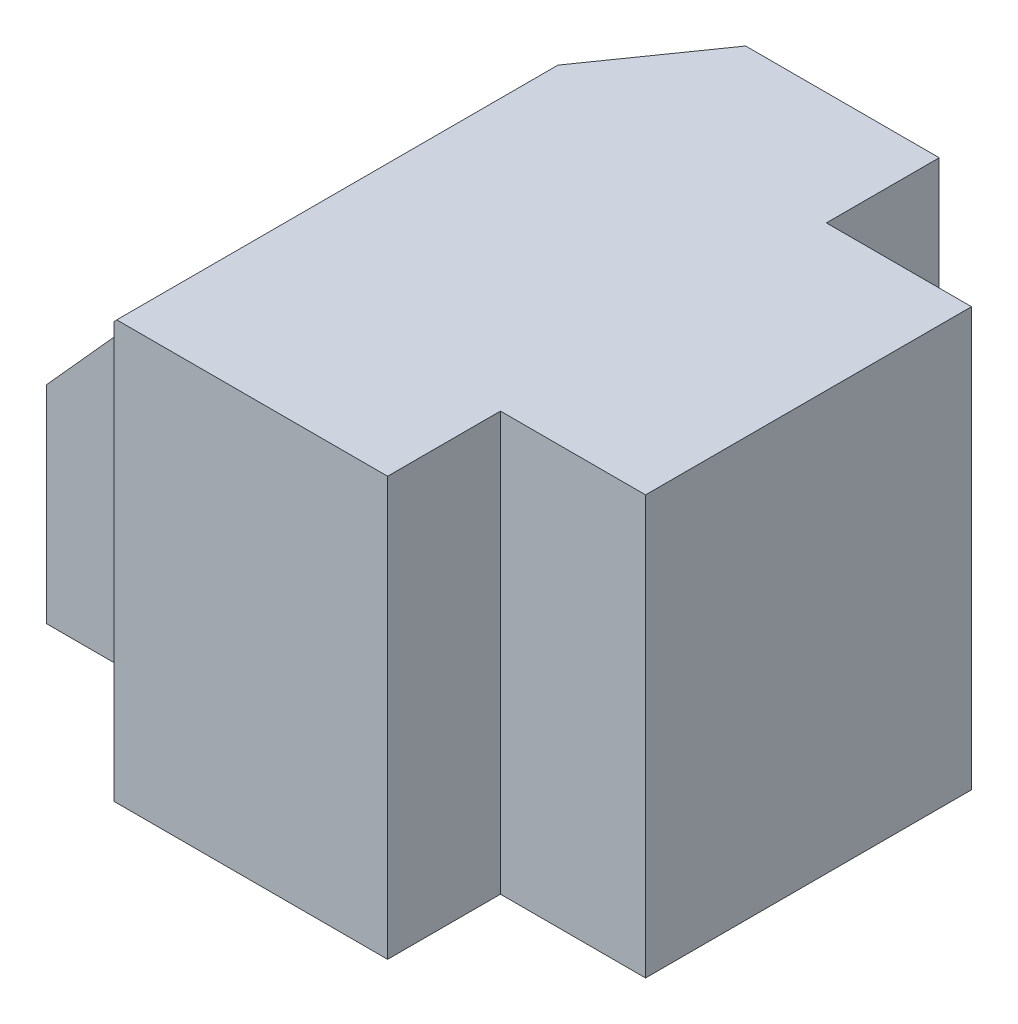
SolidWorks part; units mm, degrees
ref_plane "Front Plane" through (0, 0, 0) normal (0, 0, 1) x (1, 0, 0)
ref_plane "Top Plane" through (0, 0, 0) normal (0, 1, 0) x (1, 0, 0)
ref_plane "Right Plane" through (0, 0, 0) normal (1, 0, 0) x (0, 0, -1)
sketch "Sketch1" plane through (0, 0, 0) normal (0, 1, 0) x (1, 0, 0)
  line L0 (-131.505, 0) -> (131.505, 0) construction
  line L1 (-92.1519, -53.8673) -> (-92.1519, 53.8673)
  line L2 (-92.1519, 53.8673) -> (-27.2957, 53.8673)
  line L3 (-27.2957, 53.8673) -> (-27.2957, -53.8673)
  line L4 (-27.2957, 53.8673) -> (-27.2957, 95.4406)
  line L5 (-27.2957, 95.4406) -> (67.4596, 95.4406)
  line L6 (67.4596, 95.4406) -> (67.4596, -95.4406)
  line L7 (67.4596, 56.3956) -> (117.6766, 56.3956)
  line L8 (117.6766, 56.3956) -> (117.6766, -56.3956)
  line L9 (67.4596, -56.3956) -> (117.6766, -56.3956)
  line L10 (-27.2957, -95.4406) -> (67.4596, -95.4406)
  line L11 (-27.2957, -53.8673) -> (-27.2957, -95.4406)
  line L12 (-92.1519, -53.8673) -> (-27.2957, -53.8673)
  point P4 (0, 0)
  point P15 (117.6766, 0)
  point P16 (67.4596, 0)
  point P17 (-27.2957, 0)
  point P18 (-92.1519, 0)
extrude "Boss-Extrude1" add sketch "Sketch1" along normal blind 144.78 contours L0 L1 L12 L3 | L1 L0 L3 L2 | L3 L0 L6 L5 L4 | L0 L3 L11 L10 L6 | L6 L0 L8 L7 | L0 L6 L9 L8
chamfer "Chamfer1" distance 65.88 angle 48 1 edges at (-92.1519, 144.78, 0)
chamfer "Chamfer2" distance 27.78 angle 55 1 edges at (-27.2957, 71.8215, -95.4406)
sketch "Sketch2" plane through (0, 0, -53.8673) normal (0, 0, -1) x (-1, 0, 0)
  line L4 (92.1519, 0) -> (92.1519, 71.6128)
  line L5 (92.1519, 71.6128) -> (27.2957, 143.6429)
  line L6 (27.2957, 143.6429) -> (27.2957, 0)
  line L7 (27.2957, 0) -> (92.1519, 0)
  line L8 (92.1519, 0) -> (92.1519, 71.6128)
  line L9 (92.1519, 71.6128) -> (27.2957, 143.6429)
  line L10 (27.2957, 143.6429) -> (27.2957, 0)
  line L11 (27.2957, 0) -> (92.1519, 0)
  dimension "D1" = 0
sketch "Sketch3" plane through (-44.5174, 0, -31.1714) normal (-0.8192, 0, -0.5736) x (-0.5736, 0, 0.8192)
  line L5 (-31.8101, 144.78) -> (-78.4581, 144.78)
  line L6 (-78.4581, 144.78) -> (-78.4581, 0)
  line L7 (-78.4581, 0) -> (-30.0252, 0)
  line L8 (-30.0252, 0) -> (-30.0252, 143.6429)
  line L9 (-30.0252, 143.6429) -> (-31.8101, 144.78)
  line L10 (-31.8101, 144.78) -> (-78.4581, 144.78)
  line L11 (-78.4581, 144.78) -> (-78.4581, 0)
  line L12 (-78.4581, 0) -> (-30.0252, 0)
  line L13 (-30.0252, 0) -> (-30.0252, 143.6429)
  line L14 (-30.0252, 143.6429) -> (-31.8101, 144.78)
  dimension "D1" = 0
sketch "Sketch4" plane through (0, 0, -95.4406) normal (0, 0, -1) x (-1, 0, 0)
  line L4 (-67.4596, 0) -> (-0.4843, 0)
  line L5 (-0.4843, 0) -> (-0.4843, 144.78)
  line L6 (-0.4843, 144.78) -> (-67.4596, 144.78)
  line L7 (-67.4596, 144.78) -> (-67.4596, 0)
  line L8 (-67.4596, 0) -> (-0.4843, 0)
  line L9 (-0.4843, 0) -> (-0.4843, 144.78)
  line L10 (-0.4843, 144.78) -> (-67.4596, 144.78)
  line L11 (-67.4596, 144.78) -> (-67.4596, 0)
  dimension "D1" = 0
